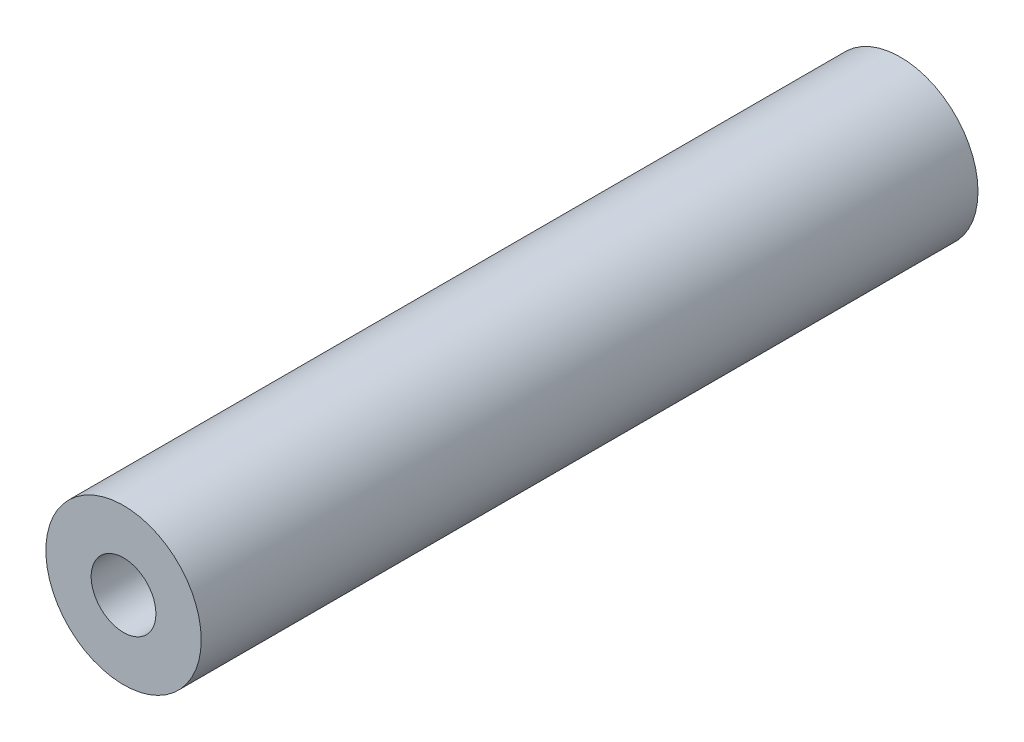
SolidWorks part; units mm, degrees
material "6061 Alloy"
ref_plane "Front Plane" through (0, 0, 0) normal (0, 0, 1) x (1, 0, 0)
ref_plane "Top Plane" through (0, 0, 0) normal (0, 1, 0) x (1, 0, 0)
ref_plane "Right Plane" through (0, 0, 0) normal (1, 0, 0) x (0, 0, -1)
sketch "Sketch1" plane through (0, 0, 0) normal (0, 0, 1) x (1, 0, 0)
  circle A0 centre (0, 0) radius 6
  circle A1 centre (0, 0) radius 3 construction
  dimension "D1" = 12
  dimension "D2" = 6
extrude "Boss-Extrude1" add sketch "Sketch1" against normal blind 30 contours A0
hole_wizard "Tap Drill for M6x1.0 Tap1" positions "3DSketch3" profile "Sketch5" hole size "M6x1.0" standard "ANSI Metric"
sketch3d "3DSketch3"
  point P0 (0, 0, 0)
  point P3 (0, 0, 0)
sketch "Sketch5" plane through (0, 0, 0) normal (1, 0, 0) x (0, -1, 0)
  line L0 (0, 0) -> (0, 23.5022)
  line L1 (0, 23.5022) -> (2.5, 22)
  line L2 (2.5, 22) -> (2.5, 0)
  line L5 (2.5, 0) -> (0, 0)
  line L10 (0, 23.5022) -> (-2.5, 22) construction
  line L11 (0, -6.35) -> (0, 107.95) construction
  dimension "Hole Dia." = 5
  dimension "Hole Depth" = 22
  dimension "Drill Angle" = 118
mirror "Mirror1" about plane through (0, 0, -30) normal (0, 0, 1) of "Tap Drill for M6x1.0 Tap1", "Boss-Extrude1"
